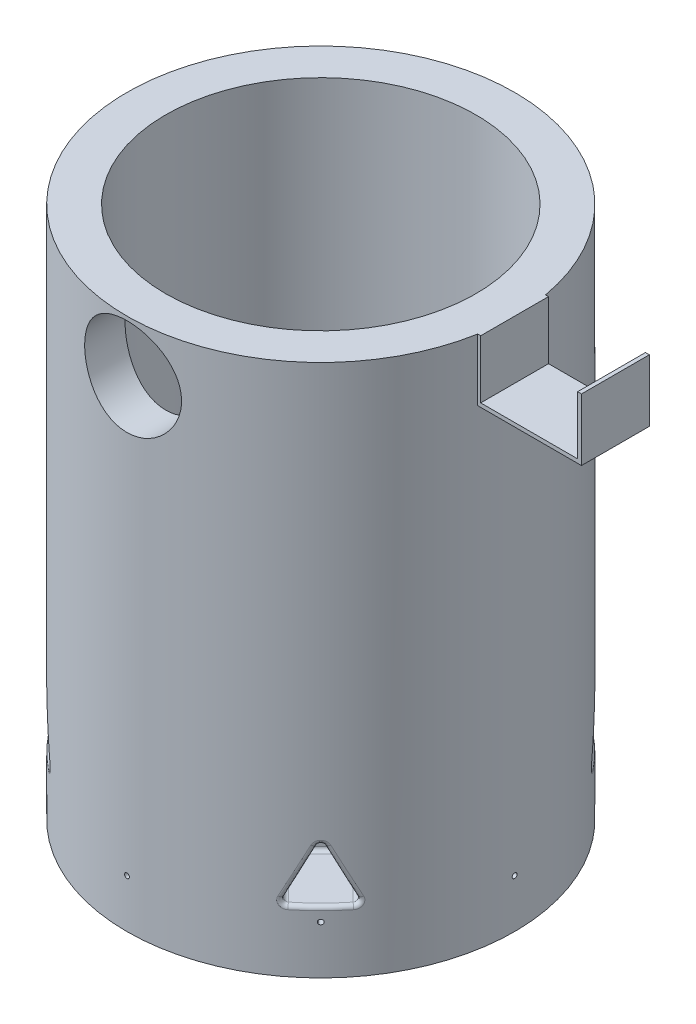
SolidWorks part; units mm, degrees
material "Cast Stainless Steel"
ref_plane "Front Plane" through (0, 0, 0) normal (0, 0, 1) x (1, 0, 0)
ref_plane "Top Plane" through (0, 0, 0) normal (0, 1, 0) x (1, 0, 0)
ref_plane "Right Plane" through (0, 0, 0) normal (1, 0, 0) x (0, 0, -1)
sketch "Sketch1" plane through (0, 0, 0) normal (0, 1, 0) x (1, 0, 0)
  circle A0 centre (0, 0) radius 127
  dimension "D1" = 254
extrude "Boss-Extrude1" add sketch "Sketch1" along normal blind 349.25
sketch "Sketch4" plane through (0, 349.25, 0) normal (0, 1, 0) x (1, 0, 0)
  circle A0 centre (0, 0) radius 101.6
  circle A1 centre (0, 0) radius 127 construction
  dimension "D1" = 203.2
extrude "Cut-Extrude1" cut sketch "Sketch4" against normal blind 269.24
ref_plane "Plane1" through (0, 0, 127) normal (0, 0, 1) x (1, 0, 0)
sketch "Sketch5" plane through (0, 0, 127) normal (0, 0, 1) x (1, 0, 0)
  circle A0 centre (0, 314.96) radius 31.75
  dimension "D1" = 63.5
  dimension "D2" = 314.96
extrude "Cut-Extrude3" cut sketch "Sketch5" against normal up to next
sketch "Sketch7" plane through (0, 0, 127) normal (0, 0, 1) x (1, 0, 0)
  point P0 (0, 31.75)
  dimension "D1" = 31.75
hole_wizard "1/8 (0.125) Diameter Hole1" positions "Sketch8" profile "Sketch9" hole size "1/8" standard "ANSI Inch"
sketch "Sketch8" plane through (0, 0, 127) normal (0, 0, 1) x (1, 0, 0)
  point P0 (0, 31.75)
sketch "Sketch9" plane through (0, 31.75, 127) normal (1, 0, 0) x (0, -1, 0)
  line L0 (0, 0) -> (0, 39.0539)
  line L1 (0, 39.0539) -> (1.5875, 38.1)
  line L2 (1.5875, 38.1) -> (1.5875, 0)
  line L5 (1.5875, 0) -> (0, 0)
  line L10 (0, 39.0539) -> (-1.5875, 38.1) construction
  line L11 (0, -6.35) -> (0, 107.95) construction
  dimension "Hole Dia." = 3.175
  dimension "Hole Depth" = 38.1
  dimension "Drill Angle" = 118
sketch "Sketch10" plane through (0, 0, 0) normal (0, -1, 0) x (1, 0, 0)
  circle A0 centre (0, 0) radius 101.6
  circle A1 centre (0, 0) radius 127 construction
  circle A2 centre (0, 0) radius 86.36
  dimension "D1" = 203.2
  dimension "D2" = 172.72
extrude "Cut-Extrude4" cut sketch "Sketch10" against normal blind 38.1
pattern_circular "CirPattern1" count 8 over 360 about axis through (0, 349.25, 0) along (0, -1, 0) of "1/8 (0.125) Diameter Hole1"
sketch "Sketch12" plane through (0, 0, 0) normal (0, 1, 0) x (1, 0, 0)
  line L0 (-89.8026, -89.8026) -> (89.8026, 89.8026)
  line L1 (0, 0) -> (25.4, 0)
  point P2 (0, 0)
  dimension "D1" = 254
  dimension "D2" = 45
  dimension "D3" = 25.4
ref_plane "Plane2" through (0, 0, 0) normal (0.7071, 0, 0.7071) x (0.7071, 0, -0.7071)
ref_plane "Plane3" through (89.8026, 0, 89.8026) normal (0.7071, 0, 0.7071) x (0.7071, 0, -0.7071)
sketch "Sketch13" plane through (89.8026, 0, 89.8026) normal (0.7071, 0, 0.7071) x (0.7071, 0, -0.7071)
  line L0 (-19.05, 40.64) -> (19.05, 40.64)
  line L1 (-19.05, 40.64) -> (0, 78.74)
  line L2 (0, 78.74) -> (19.05, 40.64)
  point P2 (0, 40.64)
  dimension "D1" = 38.1
  dimension "D2" = 38.1
  dimension "D3" = 38.1
  dimension "D4" = 40.64
extrude "Cut-Extrude5" cut sketch "Sketch13" against normal blind 44.45
pattern_circular "CirPattern2" count 4 over 360 about axis through (0, 0, 0) along (0, 1, 0) of "Cut-Extrude5"
sketch "Sketch14" plane through (0, 0, 0) normal (0, 0, 1) x (1, 0, 0)
  line L0 (127, 349.25) -> (127, 311.15)
  line L1 (127, 33.3374) -> (127, 349.25) construction
  line L2 (127, 311.15) -> (190.5, 311.15)
  line L3 (190.5, 311.15) -> (190.5, 349.25)
  dimension "D1" = 63.5
  dimension "D3" = 38.1
extrude "Extrude-Thin1" add sketch "Sketch14" along normal mid plane 44.45 thin
fillet "Fillet1" radius 2.54 36 edges at (96.3025, 59.6359, 82.7939) (65.1069, 59.69, 51.6365) (89.8026, 40.64, 89.8026) (58.3717, 40.64, 58.3717) (87.0495, 40.64, 60.1087) (82.7939, 59.6359, 96.3025) (74.0871, 78.74, 74.0871) (51.6365, 59.69, 65.1069) (60.1087, 40.64, 87.0495) (89.8026, 40.64, -89.8026) (82.7939, 59.6359, -96.3025) (96.3025, 59.6359, -82.7939) (74.0871, 78.74, -74.0871) (65.1069, 59.69, -51.6365) (87.0495, 40.64, -60.1087) (-96.3025, 59.6359, -82.7939) (-65.1069, 59.69, -51.6365) (-89.8026, 40.64, -89.8026) (-58.3717, 40.64, -58.3717) (-87.0495, 40.64, -60.1087) (-82.7939, 59.6359, -96.3025) (-74.0871, 78.74, -74.0871) (-51.6365, 59.69, -65.1069) (-60.1087, 40.64, -87.0495) (-96.3025, 59.6359, 82.7939) (-82.7939, 59.6359, 96.3025) (-51.6365, 59.69, 65.1069) (-74.0871, 78.74, 74.0871) (-89.8026, 40.64, 89.8026) (-87.0495, 40.64, 60.1087) (-58.3717, 40.64, 58.3717) (-60.1087, 40.64, 87.0495) (58.3717, 40.64, -58.3717) (60.1087, 40.64, -87.0495) (51.6365, 59.69, -65.1069) (-65.1069, 59.69, 51.6365)
